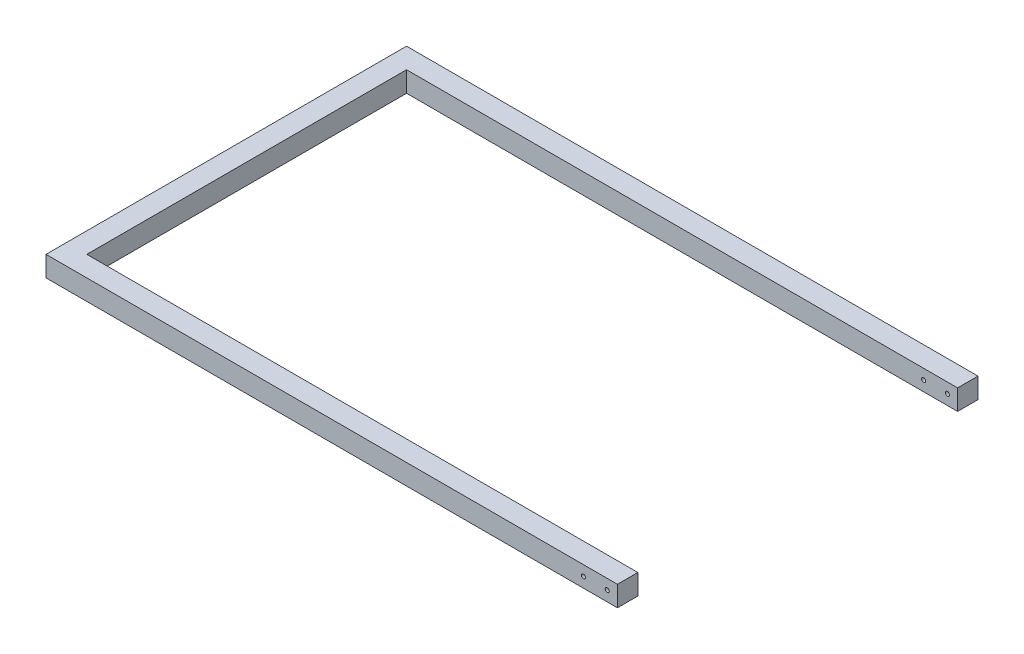
SolidWorks part; units mm, degrees
ref_plane "前视基准面" through (0, 0, 0) normal (0, 0, 1) x (1, 0, 0)
ref_plane "上视基准面" through (0, 0, 0) normal (0, 1, 0) x (1, 0, 0)
ref_plane "右视基准面" through (0, 0, 0) normal (1, 0, 0) x (0, 0, -1)
sketch "草图1" plane through (0, 0, 0) normal (0, 1, 0) x (1, 0, 0)
  line L1 (-990, 265) -> (990, 265)
  line L2 (-990, 265) -> (-990, -265)
  line L3 (-990, -265) -> (990, -265)
  line L4 (990, 265) -> (990, -265)
  line L5 (-990, 265) -> (990, -265) construction
  line L6 (-990, -265) -> (990, 265) construction
  line L7 (-960, 235) -> (960, 235)
  line L8 (-960, 235) -> (-960, -235)
  line L9 (-960, -235) -> (960, -235)
  line L10 (960, 235) -> (960, -235)
  line L11 (-960, 235) -> (960, -235) construction
  line L12 (-960, -235) -> (960, 235) construction
  point P0 (0, 0)
  point P6 (0, 0)
  dimension "D1" = 1980
  dimension "D2" = 530
  dimension "D3" = 30
  dimension "D4" = 30
extrude "凸台-拉伸1" add sketch "草图1" along normal blind 30
sketch "草图2" plane through (0, 0, 0) normal (0, -1, 0) x (1, 0, 0)
  line L0 (0, 439.6423) -> (0, -491.4203) construction
  line L1 (-990, 265) -> (990, 265) construction
  line L2 (-34, 265) -> (34, 265)
  line L3 (-34, 265) -> (-34, 235)
  line L4 (-34, 235) -> (34, 235)
  line L5 (34, 265) -> (34, 235)
  line L6 (-960, 235) -> (960, 235) construction
  line L7 (960, -235) -> (-960, -235) construction
  line L8 (-34, -235) -> (34, -235)
  line L9 (-34, -235) -> (-34, -265)
  line L10 (-34, -265) -> (34, -265)
  line L11 (34, -235) -> (34, -265)
  line L12 (990, -265) -> (-990, -265) construction
  dimension "D1" = 68
  dimension "D2" = 34
  dimension "D3" = 68
  dimension "D4" = 34
extrude "凸台-拉伸2" add sketch "草图2" along normal blind 68
sketch "草图3" plane through (0, 0, 265) normal (0, 0, 1) x (1, 0, 0)
  line L0 (34, -68) -> (-34, -68) construction
  circle A0 centre (0, -30) radius 23.5
  dimension "D1" = 47
  dimension "D2" = 38
extrude "切除-拉伸1" cut sketch "草图3" against normal through all
sketch "草图4" plane through (0, 30, 0) normal (0, 1, 0) x (1, 0, 0)
  line L0 (960, 235) -> (-960, 235) construction
  line L1 (749, 235) -> (780, 235)
  line L2 (749, 235) -> (749, -235)
  line L3 (749, -235) -> (780, -235)
  line L4 (780, 235) -> (780, -235)
  line L5 (-960, -235) -> (960, -235) construction
  line L6 (960, -235) -> (960, 235) construction
  dimension "D1" = 31
  dimension "D2" = 180
extrude "凸台-拉伸3" add sketch "草图4" against normal up to surface (30 mm away) up to face at (504.5, 0, 0)
sketch "草图5" plane through (0, 30, 0) normal (0, 1, 0) x (1, 0, 0)
  line L0 (759, 180) -> (774.5, 180) construction
  line L1 (749, 235) -> (749, -235) construction
  line L2 (780, -235) -> (780, 235) construction
  line L3 (-200.9007, 0) -> (293.2172, 0) construction
  circle A0 centre (759, 180) radius 3
  circle A1 centre (774.5, 180) radius 3
  circle A2 centre (759, -180) radius 3
  circle A3 centre (774.5, -180) radius 3
  dimension "D1" = 6
  dimension "D2" = 6
  dimension "D3" = 10
  dimension "D4" = 5.5
  dimension "D5" = 180
extrude "切除-拉伸2" cut sketch "草图5" against normal through all
sketch "草图6" plane through (0, 30, 0) normal (0, 1, 0) x (1, 0, 0)
  line L0 (900.6933, -265) -> (900.6933, -235) construction
  line L1 (-990, -265) -> (990, -265) construction
  line L2 (780, -235) -> (960, -235) construction
  line L3 (990, -265) -> (990, 265) construction
  circle A0 centre (840, -250) radius 3
  dimension "D1" = 6
  dimension "D2" = 150
extrude "切除-拉伸3" cut sketch "草图6" against normal through all and the other way through all
mirror "镜向1" about plane through (0, 0, 0) normal (0, 0, 1) of "切除-拉伸3"
sketch "草图7" plane through (0, 0, 265) normal (0, 0, 1) x (1, 0, 0)
  line L0 (0, 235.57) -> (0, -259.849) construction
  line L1 (-150, 30) -> (-150, 0)
  line L2 (-990, 30) -> (990, 30) construction
  line L3 (-990, 0) -> (-34, 0) construction
  line L4 (-150, 30) -> (1110.2453, 30)
  line L5 (1110.2453, 30) -> (1110.2453, 0)
  line L6 (1110.2453, 0) -> (-150, 0)
  dimension "D1" = 150
extrude "切除-拉伸4" cut sketch "草图7" against normal through all
sketch "草图8" plane through (0, 0, 265) normal (0, 0, 1) x (1, 0, 0)
  line L0 (-150, 30) -> (-150, 0) construction
  circle A0 centre (-200, 15) radius 3
  dimension "D2" = 6
  dimension "D1" = 50
extrude "切除-拉伸5" cut sketch "草图8" against normal through all and the other way through all
sketch "草图9" plane through (0, 0, 265) normal (0, 0, 1) x (1, 0, 0)
  circle A0 centre (-165, 15) radius 3
  circle A1 centre (-200, 15) radius 3 construction
  dimension "D1" = 6
  dimension "D2" = 35
extrude "切除-拉伸6" cut sketch "草图9" against normal through all
